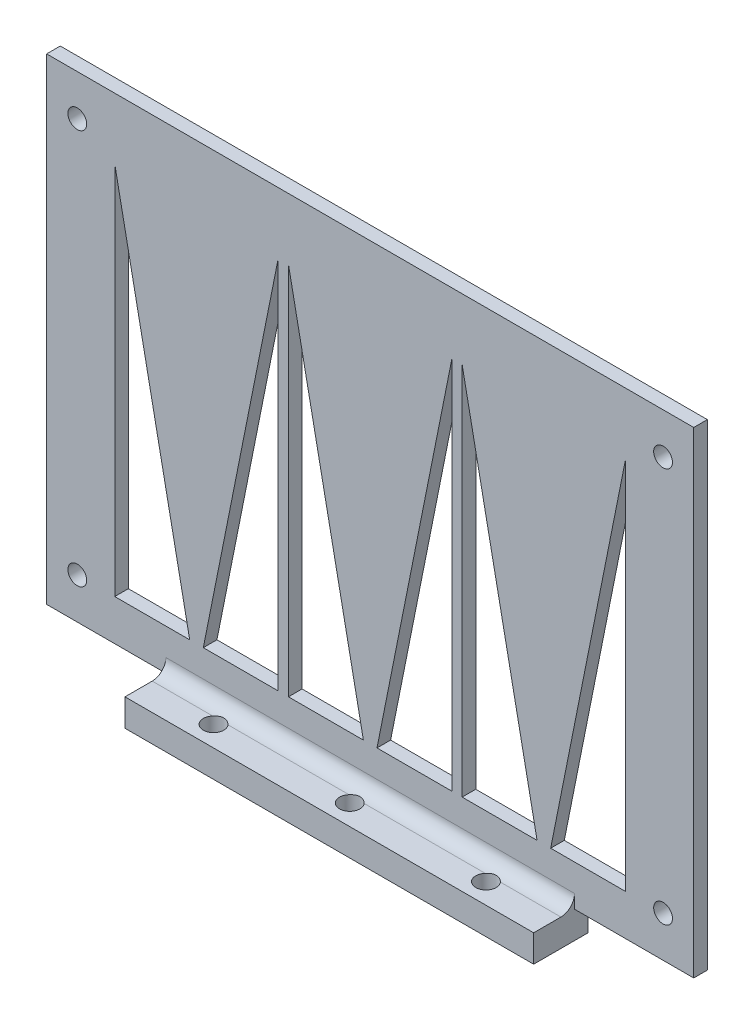
SolidWorks part; units mm, degrees
ref_plane "Front Plane" through (0, 0, 0) normal (0, 0, 1) x (1, 0, 0)
ref_plane "Top Plane" through (0, 0, 0) normal (0, 1, 0) x (1, 0, 0)
ref_plane "Right Plane" through (0, 0, 0) normal (1, 0, 0) x (0, 0, -1)
sketch "Sketch1" plane through (0, 0, 0) normal (0, 1, 0) x (1, 0, 0)
  line L1 (0, 0) -> (60, 0)
  line L2 (0, 0) -> (0, 8)
  line L3 (0, 8) -> (60, 8)
  line L4 (60, 0) -> (60, 8)
  dimension "D1" = 8
  dimension "D2" = 60
extrude "Boss-Extrude1" add sketch "Sketch1" along normal blind 4
sketch "Sketch3" plane through (0, 0, -8) normal (0, 0, -1) x (-1, 0, 0)
  line L0 (0, 4) -> (-60, 4) construction
  line L1 (17.5, 4) -> (-77.5, 4)
  line L2 (17.5, 4) -> (17.5, 74)
  line L3 (17.5, 74) -> (-77.5, 74)
  line L4 (-77.5, 4) -> (-77.5, 74)
  line L6 (-3.5, 10) -> (7.5, 65)
  line L7 (13, 68) -> (-73, 68) construction
  line L8 (13, 68) -> (13, 10) construction
  line L9 (13, 10) -> (-73, 10) construction
  line L10 (-73, 68) -> (-73, 10) construction
  line L11 (7.5, 65) -> (7.5, 10)
  line L12 (7.5, 10) -> (-3.5, 10)
  line L13 (-4.5, 74) -> (-4.5, 0) construction
  line L14 (0, 0) -> (-60, 0) construction
  line L15 (-16.5, 10) -> (-5.5, 10)
  line L16 (-5.5, 10) -> (-16.5, 65)
  line L17 (-16.5, 65) -> (-16.5, 10)
  line L18 (-18, 10) -> (-29, 10)
  line L19 (-29, 10) -> (-18, 65)
  line L20 (-18, 65) -> (-18, 10)
  line L21 (-42, 10) -> (-31, 10)
  line L22 (-31, 10) -> (-42, 65)
  line L23 (-42, 65) -> (-42, 10)
  line L24 (-43.5, 10) -> (-54.5, 10)
  line L25 (-54.5, 10) -> (-43.5, 65)
  line L26 (-43.5, 65) -> (-43.5, 10)
  line L27 (-67.5, 10) -> (-56.5, 10)
  line L28 (-56.5, 10) -> (-67.5, 65)
  line L29 (-67.5, 65) -> (-67.5, 10)
  line L30 (-60, 4) -> (0, 4) construction
  circle A0 centre (13, 68) radius 1.38
  circle A1 centre (-73, 68) radius 1.38
  circle A2 centre (-73, 10) radius 1.38
  circle A3 centre (13, 10) radius 1.38
  point P9 (-30, 4)
  point P12 (-30, 10)
  point P13 (-30, 4)
  point P14 (13, 39)
  point P15 (17.5, 39)
  dimension "D5" = 2.76
  dimension "D1" = 95
  dimension "D2" = 70
  dimension "D3" = 86
  dimension "D4" = 58
  dimension "D6" = 55
  dimension "D7" = 6
  dimension "D8" = 10
  dimension "D9" = 2
  dimension "10" = 11
  dimension "D10" = 1
  dimension "D12" = 10
  dimension "D11" = 3
  dimension "D13" = 2
extrude "Boss-Extrude2" add sketch "Sketch3" against normal blind 2
fillet "Fillet3" radius 2 1 edges at (30, 4, -6)
hole_wizard "Ø3.0mm Dowel Hole2" positions "Sketch6" profile "Sketch7" hole size "Ø3.0" standard "ANSI Metric" end condition through all
sketch "Sketch6" plane through (0, 74, 0) normal (0, 1, 0) x (1, 0, 0)
  line L0 (-17.5, 8) -> (77.5, 8) construction
  point P0 (10, 3)
  point P2 (30, 3)
  point P4 (50, 3)
  point P12 (30, 8)
  dimension "D1" = 5
  dimension "D2" = 40
  dimension "D3" = 20
sketch "Sketch7" plane through (10, 74, -3) normal (1, 0, 0) x (0, 0, 1)
  line L0 (0, 0) -> (0, 74)
  line L1 (0, 74) -> (1.5, 74)
  line L2 (1.5, 74) -> (1.5, 0)
  line L5 (1.5, 0) -> (0, 0)
  line L11 (0, -6.35) -> (0, 107.95) construction
  dimension "Thru Hole Dia." = 3
  dimension "Thru Hole Depth" = 74
